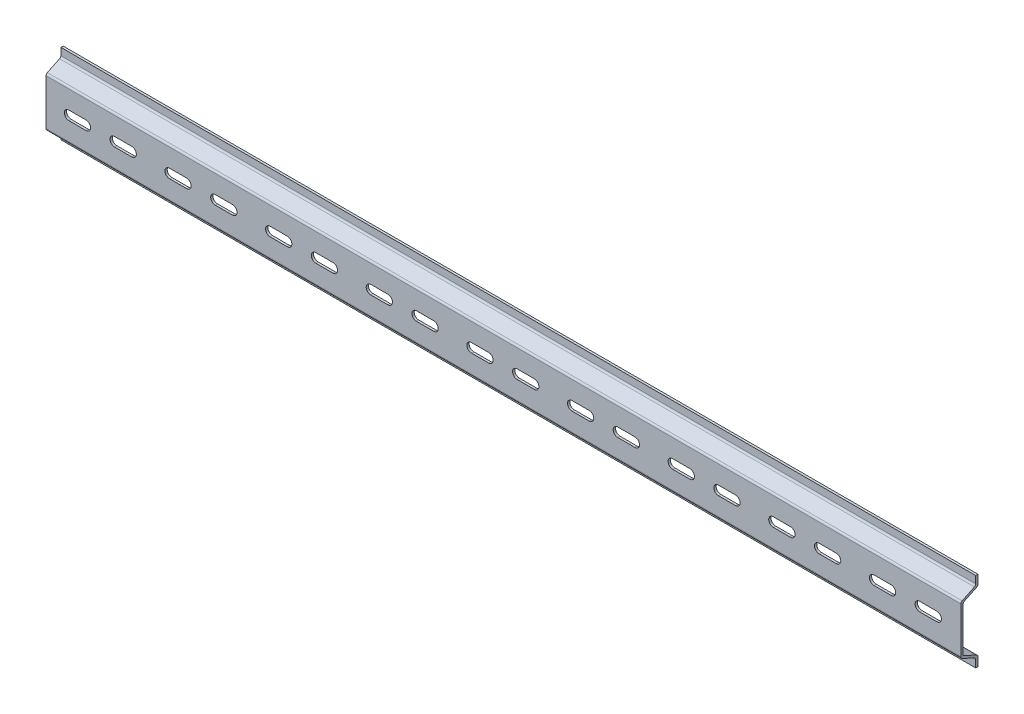
SolidWorks part; units mm, degrees
ref_plane "前视基准面" through (0, 0, 0) normal (0, 0, 1) x (1, 0, 0)
ref_plane "上视基准面" through (0, 0, 0) normal (0, 1, 0) x (1, 0, 0)
ref_plane "右视基准面" through (0, 0, 0) normal (1, 0, 0) x (0, 0, -1)
sketch "草图1" plane through (0, 0, 0) normal (1, 0, 0) x (0, 0, -1)
  line L0 (0, -10) -> (0, 10)
  line L1 (0, 10) -> (6.5, 13.1208)
  line L2 (6.5, 13.1208) -> (6.5, 17.5)
  line L3 (6.5, 17.5) -> (5.5, 17.5)
  line L4 (5.5, 17.5) -> (5.5, 13.75)
  line L5 (5.5, 13.75) -> (-1, 10.6292)
  line L6 (-1, 10.6292) -> (-1, -10.6292)
  line L7 (-14.3812, 0) -> (24.228, 0) construction
  line L8 (5.5, -13.75) -> (-1, -10.6292)
  line L9 (5.5, -17.5) -> (5.5, -13.75)
  line L10 (6.5, -17.5) -> (5.5, -17.5)
  line L11 (6.5, -13.1208) -> (6.5, -17.5)
  line L12 (0, -10) -> (6.5, -13.1208)
  point P12 (-1, 0)
  point P17 (0, 0)
  dimension "D1" = 7.5
  dimension "D2" = 1
  dimension "D3" = 1
  dimension "D4" = 1
  dimension "D5" = 27.5
  dimension "D6" = 35
  dimension "D7" = 20
extrude "凸台-拉伸1" add sketch "草图1" along normal blind 400
fillet "圆角1" radius 1 7 edges at (200, 13.75, -5.5) (200, 10.6292, 1) (200, 10, 0) (200, -10.6292, 1) (200, -13.1208, -6.5) (200, -13.75, -5.5) (200, 13.1208, -6.5)
sketch "草图2" plane through (0, 0, 0) normal (0, 0, -1) x (-1, 0, 0)
  line L0 (33.4315, 0) -> (-53.4315, 0) construction
  line L1 (-10, 0) -> (-17.5, 0) construction
  line L2 (-10, -2) -> (-17.5, -2)
  line L3 (-10, 2) -> (-17.5, 2)
  line L4 (-30, 0) -> (-37.5, 0) construction
  line L5 (-30, -2) -> (-37.5, -2)
  line L6 (-30, 2) -> (-37.5, 2)
  line L7 (-54, 0) -> (-61.5, 0) construction
  line L8 (-54, -2) -> (-61.5, -2)
  line L9 (-54, 2) -> (-61.5, 2)
  line L10 (-74, 0) -> (-81.5, 0) construction
  line L11 (-74, -2) -> (-81.5, -2)
  line L12 (-74, 2) -> (-81.5, 2)
  line L13 (-98, 0) -> (-105.5, 0) construction
  line L14 (-98, -2) -> (-105.5, -2)
  line L15 (-98, 2) -> (-105.5, 2)
  line L16 (-118, 0) -> (-125.5, 0) construction
  line L17 (-118, -2) -> (-125.5, -2)
  line L18 (-118, 2) -> (-125.5, 2)
  line L19 (-142, 0) -> (-149.5, 0) construction
  line L20 (-142, -2) -> (-149.5, -2)
  line L21 (-142, 2) -> (-149.5, 2)
  line L22 (-162, 0) -> (-169.5, 0) construction
  line L23 (-162, -2) -> (-169.5, -2)
  line L24 (-162, 2) -> (-169.5, 2)
  line L25 (-186, 0) -> (-193.5, 0) construction
  line L26 (-186, -2) -> (-193.5, -2)
  line L27 (-186, 2) -> (-193.5, 2)
  line L28 (-206, 0) -> (-213.5, 0) construction
  line L29 (-206, -2) -> (-213.5, -2)
  line L30 (-206, 2) -> (-213.5, 2)
  line L31 (-230, 0) -> (-237.5, 0) construction
  line L32 (-230, -2) -> (-237.5, -2)
  line L33 (-230, 2) -> (-237.5, 2)
  line L34 (-250, 0) -> (-257.5, 0) construction
  line L35 (-250, -2) -> (-257.5, -2)
  line L36 (-250, 2) -> (-257.5, 2)
  line L37 (-274, 0) -> (-281.5, 0) construction
  line L38 (-274, -2) -> (-281.5, -2)
  line L39 (-274, 2) -> (-281.5, 2)
  line L40 (-294, 0) -> (-301.5, 0) construction
  line L41 (-294, -2) -> (-301.5, -2)
  line L42 (-294, 2) -> (-301.5, 2)
  line L43 (-318, 0) -> (-325.5, 0) construction
  line L44 (-318, -2) -> (-325.5, -2)
  line L45 (-318, 2) -> (-325.5, 2)
  line L46 (-338, 0) -> (-345.5, 0) construction
  line L47 (-338, -2) -> (-345.5, -2)
  line L48 (-338, 2) -> (-345.5, 2)
  line L49 (-362, 0) -> (-369.5, 0) construction
  line L50 (-362, -2) -> (-369.5, -2)
  line L51 (-362, 2) -> (-369.5, 2)
  line L52 (-382, 0) -> (-389.5, 0) construction
  line L53 (-382, -2) -> (-389.5, -2)
  line L54 (-382, 2) -> (-389.5, 2)
  arc A0 (-10, -2) -> (-10, 2) centre (-10, 0) ccw
  arc A1 (-17.5, 2) -> (-17.5, -2) centre (-17.5, 0) ccw
  arc A2 (-30, -2) -> (-30, 2) centre (-30, 0) ccw
  arc A3 (-37.5, 2) -> (-37.5, -2) centre (-37.5, 0) ccw
  arc A4 (-54, -2) -> (-54, 2) centre (-54, 0) ccw
  arc A5 (-61.5, 2) -> (-61.5, -2) centre (-61.5, 0) ccw
  arc A6 (-74, -2) -> (-74, 2) centre (-74, 0) ccw
  arc A7 (-81.5, 2) -> (-81.5, -2) centre (-81.5, 0) ccw
  arc A8 (-98, -2) -> (-98, 2) centre (-98, 0) ccw
  arc A9 (-105.5, 2) -> (-105.5, -2) centre (-105.5, 0) ccw
  arc A10 (-118, -2) -> (-118, 2) centre (-118, 0) ccw
  arc A11 (-125.5, 2) -> (-125.5, -2) centre (-125.5, 0) ccw
  arc A12 (-142, -2) -> (-142, 2) centre (-142, 0) ccw
  arc A13 (-149.5, 2) -> (-149.5, -2) centre (-149.5, 0) ccw
  arc A14 (-162, -2) -> (-162, 2) centre (-162, 0) ccw
  arc A15 (-169.5, 2) -> (-169.5, -2) centre (-169.5, 0) ccw
  arc A16 (-186, -2) -> (-186, 2) centre (-186, 0) ccw
  arc A17 (-193.5, 2) -> (-193.5, -2) centre (-193.5, 0) ccw
  arc A18 (-206, -2) -> (-206, 2) centre (-206, 0) ccw
  arc A19 (-213.5, 2) -> (-213.5, -2) centre (-213.5, 0) ccw
  arc A20 (-230, -2) -> (-230, 2) centre (-230, 0) ccw
  arc A21 (-237.5, 2) -> (-237.5, -2) centre (-237.5, 0) ccw
  arc A22 (-250, -2) -> (-250, 2) centre (-250, 0) ccw
  arc A23 (-257.5, 2) -> (-257.5, -2) centre (-257.5, 0) ccw
  arc A24 (-274, -2) -> (-274, 2) centre (-274, 0) ccw
  arc A25 (-281.5, 2) -> (-281.5, -2) centre (-281.5, 0) ccw
  arc A26 (-294, -2) -> (-294, 2) centre (-294, 0) ccw
  arc A27 (-301.5, 2) -> (-301.5, -2) centre (-301.5, 0) ccw
  arc A28 (-318, -2) -> (-318, 2) centre (-318, 0) ccw
  arc A29 (-325.5, 2) -> (-325.5, -2) centre (-325.5, 0) ccw
  arc A30 (-338, -2) -> (-338, 2) centre (-338, 0) ccw
  arc A31 (-345.5, 2) -> (-345.5, -2) centre (-345.5, 0) ccw
  arc A32 (-362, -2) -> (-362, 2) centre (-362, 0) ccw
  arc A33 (-369.5, 2) -> (-369.5, -2) centre (-369.5, 0) ccw
  arc A34 (-382, -2) -> (-382, 2) centre (-382, 0) ccw
  arc A35 (-389.5, 2) -> (-389.5, -2) centre (-389.5, 0) ccw
  point P5 (-13.75, 0)
  point P14 (-33.75, 0)
  point P21 (-57.75, 0)
  point P28 (-77.75, 0)
  point P35 (-101.75, 0)
  point P42 (-121.75, 0)
  point P49 (-145.75, 0)
  point P56 (-165.75, 0)
  point P63 (-189.75, 0)
  point P70 (-209.75, 0)
  point P77 (-233.75, 0)
  point P84 (-253.75, 0)
  point P91 (-277.75, 0)
  point P98 (-297.75, 0)
  point P105 (-321.75, 0)
  point P112 (-341.75, 0)
  point P119 (-365.75, 0)
  point P126 (-385.75, 0)
  dimension "D1" = 2
  dimension "D2" = 7.5
  dimension "D3" = 10
  dimension "D4" = 2
  dimension "D5" = 9
extrude "切除-拉伸1" cut sketch "草图2" against normal blind 10
